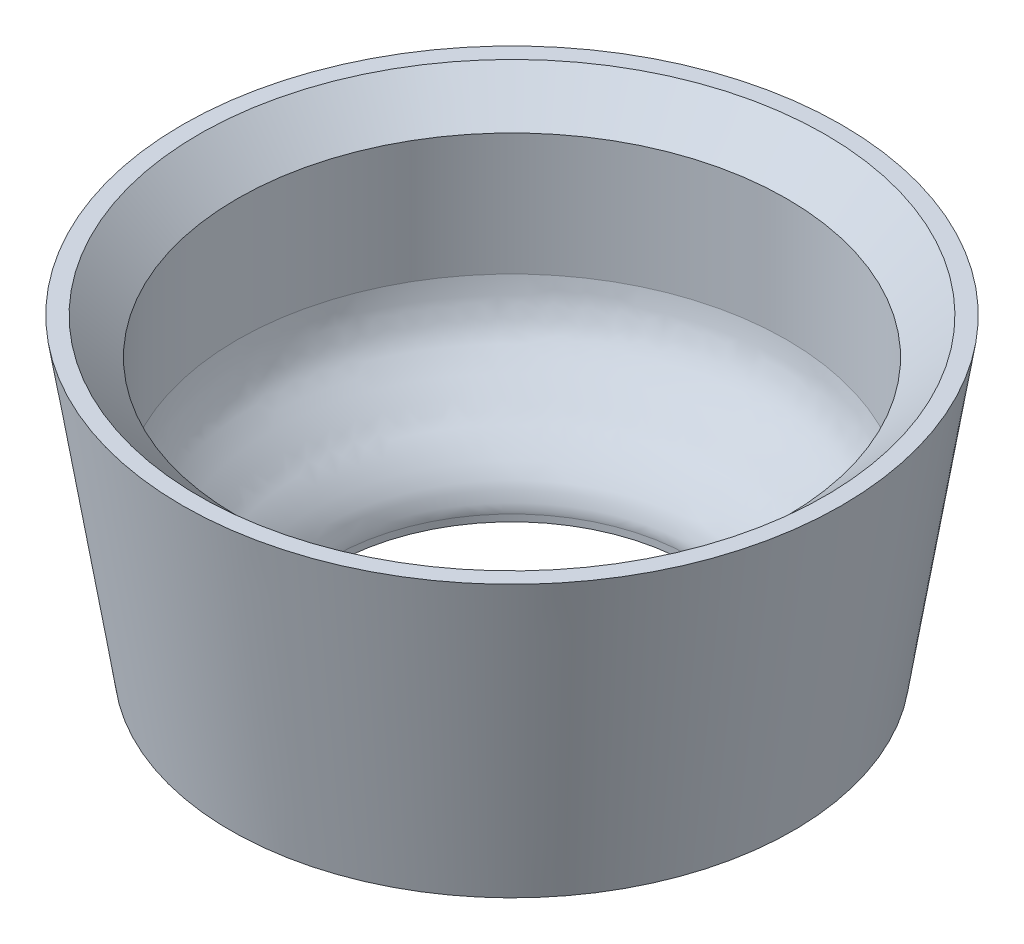
SolidWorks part; units mm, degrees
ref_plane "Front Plane" through (0, 0, 0) normal (0, 0, 1) x (1, 0, 0)
ref_plane "Top Plane" through (0, 0, 0) normal (0, 1, 0) x (1, 0, 0)
ref_plane "Right Plane" through (0, 0, 0) normal (1, 0, 0) x (0, 0, -1)
sketch "Sketch1" plane through (0, 0, 0) normal (1, 0, 0) x (0, 0, -1)
  line L0 (26.0878, 274.978) -> (26.0878, 232.1195) construction
  line L2 (40.135, 302.9291) -> (40.135, 295.6281) construction
  line L5 (0, 324) -> (3.2968, 324) construction
  line L7 (21.6442, 186.0993) -> (0, 186.0993) construction
  line L9 (26.0878, 262.3641) -> (26.0878, 259.4973) construction
  line L16 (0, 0) -> (51.9362, 327.9125) construction
  line L17 (0, 324) -> (0, 332) construction
  line L18 (26.0878, 274.978) -> (26.0878, 268.978) construction
  line L19 (26.0878, 268.978) -> (26.0878, 248.978) construction
  line L20 (26.0878, 268.978) -> (42.6019, 268.978) construction
  line L21 (26.0878, 274.978) -> (43.5522, 274.978) construction
  line L22 (26.0878, 248.978) -> (39.4342, 248.978) construction
  line L23 (0, 0) -> (-51.9362, 327.9125) construction
  line L24 (-47.4003, 299.274) -> (-47.4003, 268.978) construction
  line L25 (-47.4003, 268.978) -> (-42.6019, 268.978) construction
  line L26 (40.135, 295.6281) -> (40.435, 295.6281) construction
  line L27 (0, 76.96) -> (400, 76.96) construction
  line L28 (0, 76.96) -> (-400, 76.96) construction
  line L29 (-200, 76.96) -> (-200, 183.96) construction
  line L30 (200, 76.96) -> (200, 183.96) construction
  line L31 (-200, 183.96) -> (-200, 182.57) construction
  line L32 (-200, 182.57) -> (400, 182.57) construction
  line L33 (-200, 182.57) -> (-400, 182.57) construction
  line L36 (21.6442, 186.0993) -> (21.6442, 226.0993) construction
  line L37 (0, 324) -> (0, 186.1152) construction
  line L38 (0, 186.1152) -> (0, 186.0993)
  line L39 (0, 0) -> (-2, 0) construction
  line L40 (-2, 0) -> (49.9843, 328.2157) construction
  line L41 (51.9362, 327.9125) -> (49.9362, 327.9125) construction
  line L42 (26.0878, 274.978) -> (26.3878, 274.978) construction
  line L43 (26.0878, 274.978) -> (26.0878, 273.978) construction
  line L44 (26.2311, 276.2681) -> (26.5311, 276.2681) construction
  line L45 (26.6611, 277.4147) -> (26.9611, 277.4147) construction
  line L46 (27.2344, 278.5614) -> (27.5344, 278.5614) construction
  line L47 (27.9512, 279.4215) -> (28.2512, 279.4215) construction
  line L48 (28.9545, 280.5682) -> (29.2545, 280.5682) construction
  line L49 (29.8146, 281.4282) -> (30.1146, 281.4282) construction
  line L50 (30.8179, 282.4316) -> (31.1179, 282.4316) construction
  line L51 (31.8213, 283.2917) -> (32.1213, 283.2917) construction
  line L52 (32.8246, 284.2951) -> (33.1246, 284.2951) construction
  line L53 (33.8281, 285.2984) -> (34.1281, 285.2984) construction
  line L54 (34.9748, 286.3018) -> (35.2748, 286.3018) construction
  line L55 (35.9781, 287.3051) -> (36.2781, 287.3051) construction
  line L56 (36.8382, 288.1652) -> (37.1382, 288.1652) construction
  line L57 (37.8416, 289.3119) -> (38.1416, 289.3119) construction
  line L58 (38.5582, 290.4586) -> (38.8582, 290.4586) construction
  line L59 (39.1315, 291.7487) -> (39.4315, 291.7487) construction
  line L60 (39.5617, 292.8954) -> (39.8617, 292.8954) construction
  line L61 (39.8483, 294.0421) -> (40.1483, 294.0421) construction
  line L63 (40.135, 302.9291) -> (40.435, 302.9291) construction
  line L64 (26.0878, 273.978) -> (26.3878, 273.978) construction
  line L68 (0, 332) -> (36.0261, 332) construction
  line L69 (36.0261, 332) -> (36.0261, 309.4264) construction
  line L70 (36.0261, 309.4264) -> (48.951, 321.6917) construction
  line L71 (36.0261, 309.4264) -> (49.0083, 309.4264) construction
  line L73 (36.0261, 309.4264) -> (46.0928, 318.9794) construction
  line L74 (46.0928, 318.9794) -> (46.0928, 386.8005) construction
  line L75 (46.0928, 318.9794) -> (19.4833, 320.3739) construction
  line L76 (19.4833, 320.3739) -> (20.8454, 323.7133) construction
  line L77 (19.4833, 320.3739) -> (28.7426, 316.597) construction
  line L78 (19.4833, 320.3739) -> (10.2239, 324.1508) construction
  line L79 (10.2239, 324.1508) -> (9.7753, 323.0511) construction
  line L80 (28.7426, 316.597) -> (28.4187, 315.803) construction
  arc A0 (-298.7691, 144.7791) -> (305.6579, 129.6043) centre (0, 0) cw construction
  spline S0 degree 3 poles (21.6442, 226.0993) (22.3362, 225.9573) (23.1249, 226.5484) (24.2443, 227.206) (25.0066, 227.971) (25.5796, 228.9526) (25.8622, 230.3928) (26.0228, 231.4438) (26.0878, 232.1195) knots 0 0 0 0 0.223849 0.348959 0.47164 0.61152 0.754586 1 1 1 1 construction
  spline S1 degree 3 poles (3.2968, 324) (4.1972, 323.8396) (5.699, 323.816) (7.6935, 323.4297) (9.2722, 323.1563) (10.7507, 322.8538) (12.1816, 322.5577) (13.6372, 322.313) (14.8643, 321.9117) (15.9115, 321.5662) (16.81, 321.2491) (17.7339, 321.0149) (18.8379, 320.6416) (19.931, 320.1935) (21.0686, 319.6948) (22.141, 319.2627) (23.2156, 318.6856) (24.4371, 318.1163) (25.6762, 317.3518) (27.1066, 316.7518) (28.4318, 315.7832) (29.7322, 314.8939) (31.058, 313.93) (32.1959, 312.8581) (33.3378, 311.8503) (34.4539, 310.9646) (35.3895, 309.8867) (36.5078, 309.0949) (37.2942, 308.0208) (38.1233, 307.1238) (38.9048, 306.0961) (39.4724, 304.6349) (40.2774, 303.734) (40.135, 302.9291) knots 0 0 0 0 0.061585 0.100795 0.136831 0.1697 0.202569 0.235438 0.269088 0.289473 0.309858 0.333319 0.353706 0.388423 0.412965 0.437514 0.46634 0.495168 0.528354 0.564387 0.59925 0.638593 0.670824 0.709635 0.743897 0.773612 0.805519 0.839783 0.864953 0.89467 0.922395 0.951224 1 1 1 1 construction
  spline S2 degree 3 poles (40.135, 295.6188) (39.9636, 294.7131) (39.7869, 293.3689) (39.1095, 291.6901) (38.6019, 290.4599) (37.8418, 289.2392) (36.9195, 288.2279) (35.9232, 287.2651) (34.974, 286.2515) (33.8311, 285.3463) (32.8233, 284.2966) (31.8701, 283.2868) (30.7668, 282.4387) (29.8742, 281.4644) (28.8604, 280.5152) (28.0567, 279.5119) (27.1438, 278.5569) (26.4968, 277.0287) (26.0081, 275.8567) (26.0878, 274.978) knots 0 0 0 0 0.108356 0.15601 0.210945 0.263562 0.322855 0.370186 0.425399 0.484692 0.539909 0.595126 0.646549 0.701764 0.749093 0.808384 0.85195 0.901837 1 1 1 1 construction
  dimension "D2" = 2
  dimension "D4" = 8
  dimension "D5" = 2
  dimension "D6" = 36.0261
  dimension "D8" = 70.809
  dimension "D9" = 6
  dimension "D10" = 20
  dimension "D11" = 1.1877
  dimension "D12" = 0.8575
  dimension "D13" = 255.04
  dimension "D14" = 107
  dimension "D15" = 107
  dimension "D16" = 332
  dimension "D17" = 105.61
  dimension "D18" = 105.61
  dimension "D19" = 40
  dimension "D20" = 90
  dimension "D21" = 46.5
sketch "cup" plane through (0, 0, 0) normal (1, 0, 0) x (0, 0, -1)
  line L0 (0, 0) -> (0, 354.6797) construction
  line L1 (26.3878, 273.978) -> (41.3938, 273.978)
  line L2 (-2, 0) -> (49.9843, 328.2157) construction
  line L4 (40.435, 302.9291) -> (40.435, 313.6103)
  line L5 (36.0261, 309.4264) -> (48.951, 321.6917) construction
  line L7 (40.435, 302.9291) -> (40.435, 295.6281)
  line L8 (26.3878, 274.978) -> (26.3878, 273.978)
  line L9 (40.435, 313.6103) -> (46.0928, 318.9794)
  line L10 (46.0928, 318.9794) -> (48.5214, 318.9794)
  line L11 (48.5214, 318.9794) -> (41.3938, 273.978)
  spline S0 degree 3 poles (26.3878, 274.978) (26.3081, 275.8567) (26.7968, 277.0287) (27.4438, 278.5569) (28.3567, 279.5119) (29.1604, 280.5152) (30.1742, 281.4644) (31.0668, 282.4387) (32.1701, 283.2868) (33.1233, 284.2966) (34.1311, 285.3463) (35.274, 286.2515) (36.2232, 287.2651) (37.2195, 288.2279) (38.1418, 289.2392) (38.9019, 290.4599) (39.4095, 291.6901) (40.088, 293.3717) (40.2647, 294.7192) (40.435, 295.6281) knots 0 0 0 0 0.098128 0.147998 0.191548 0.250818 0.29813 0.353325 0.40473 0.459928 0.515125 0.574397 0.629591 0.676904 0.736176 0.788775 0.84369 0.891328 1 1 1 1
revolve "Revolve10" add sketch "cup" angle 360 about L0
